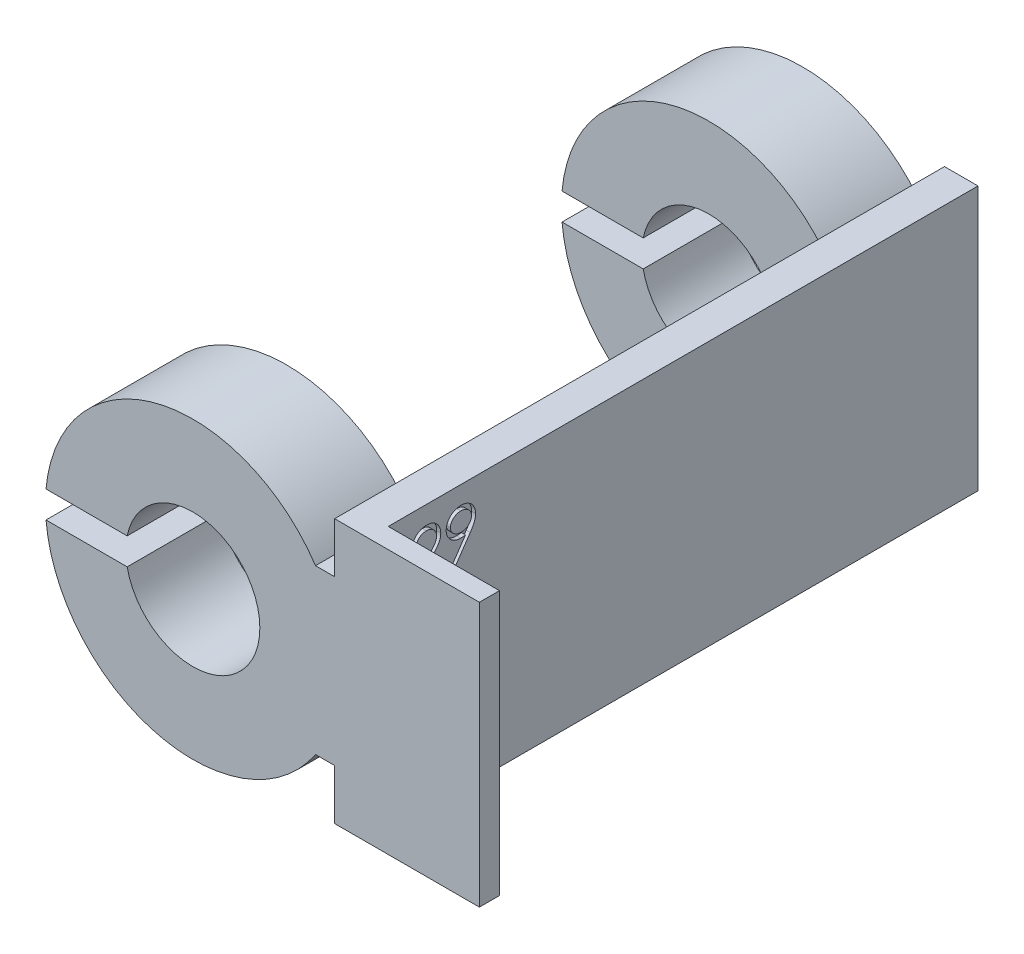
SolidWorks part; units mm, degrees
ref_plane "Front Plane" through (0, 0, 0) normal (0, 0, 1) x (1, 0, 0)
ref_plane "Top Plane" through (0, 0, 0) normal (0, 1, 0) x (1, 0, 0)
ref_plane "Right Plane" through (0, 0, 0) normal (1, 0, 0) x (0, 0, -1)
sketch "Sketch1" plane through (0, 0, 0) normal (0, 0, 1) x (1, 0, 0)
  line L2 (9.1537, 6.1) -> (10.58, 6.1)
  line L3 (-4.899, 1) -> (-10.9545, 1)
  line L4 (-4.899, -1) -> (-10.9545, -1)
  line L5 (10.58, 9.85) -> (21.38, 9.85)
  line L6 (10.58, 9.85) -> (10.58, 6.1)
  line L7 (10.58, -9.85) -> (21.38, -9.85)
  line L8 (21.38, 9.85) -> (21.38, -9.85)
  line L9 (9.1537, -6.1) -> (10.58, -6.1)
  line L10 (10.58, -6.1) -> (10.58, -9.85)
  arc A0 (-4.899, -1) -> (-4.899, 1) centre (0, 0) ccw
  arc A1 (-10.9545, -1) -> (9.1537, -6.1) centre (0, 0) ccw
  arc A2 (9.1537, 6.1) -> (-10.9545, 1) centre (0, 0) ccw
  dimension "D1" = 10
  dimension "D2" = 22
  dimension "D5" = 19.7
  dimension "D3" = 21.38
  dimension "D4" = 10.8
extrude "Boss-Extrude1" add sketch "Sketch1" along normal blind 7
sketch "Sketch4" plane through (0, -9.85, 0) normal (0, -1, 0) x (1, 0, 0)
  line L1 (21.38, 0) -> (10.58, 0) construction
  line L2 (13.08, 0) -> (13.08, 5.5)
  line L3 (13.08, 5.5) -> (21.38, 5.5)
  line L4 (21.38, 7) -> (21.38, 0) construction
  line L8 (13.08, 0) -> (21.38, 0)
  line L9 (21.38, 0) -> (21.38, 5.5)
  dimension "D3" = 8.3
extrude "Cut-Extrude1" cut sketch "Sketch4" against normal blind 24 from offset 0
sketch "Sketch5" plane through (0, -9.85, 0) normal (0, -1, 0) x (1, 0, 0)
  line L0 (10.58, 0) -> (10.58, -38.5)
  line L1 (10.58, -38.5) -> (13.08, -38.5)
  line L2 (13.08, -38.5) -> (13.08, 0)
  line L3 (10.58, 0) -> (13.08, 0)
  dimension "D1" = 38.5
extrude "Boss-Extrude2" add sketch "Sketch5" against normal blind 19.7
sketch "Sketch6" plane through (0, 0, -38.5) normal (0, 0, -1) x (-1, 0, 0)
  line L0 (0, 0) -> (-25.5199, 0) construction
sketch "Sketch7" plane through (0, 0, -38.5) normal (0, 0, -1) x (-1, 0, 0)
  line L0 (-10.58, 6.1) -> (-10.58, -6.1)
  line L1 (-10.58, -6.1) -> (-9.1537, -6.1)
  line L2 (-10.58, 6.1) -> (-9.1537, 6.1)
  line L3 (4.899, 1) -> (10.9545, 1)
  line L4 (4.899, -1) -> (10.9545, -1)
  arc A0 (4.899, 1) -> (4.899, -1) centre (0, 0) ccw
  arc A1 (10.9545, 1) -> (-9.1537, 6.1) centre (0, 0) ccw
  arc A2 (-9.1537, -6.1) -> (10.9545, -1) centre (0, 0) ccw
extrude "Boss-Extrude3" add sketch "Sketch7" against normal blind 7
sketch "Sketch8" plane through (13.08, 0, 0) normal (1, 0, 0) x (0, 0, -1)
  text T0 "29"
extrude "Cut-Extrude2" cut sketch "Sketch8" against normal blind 0.3
